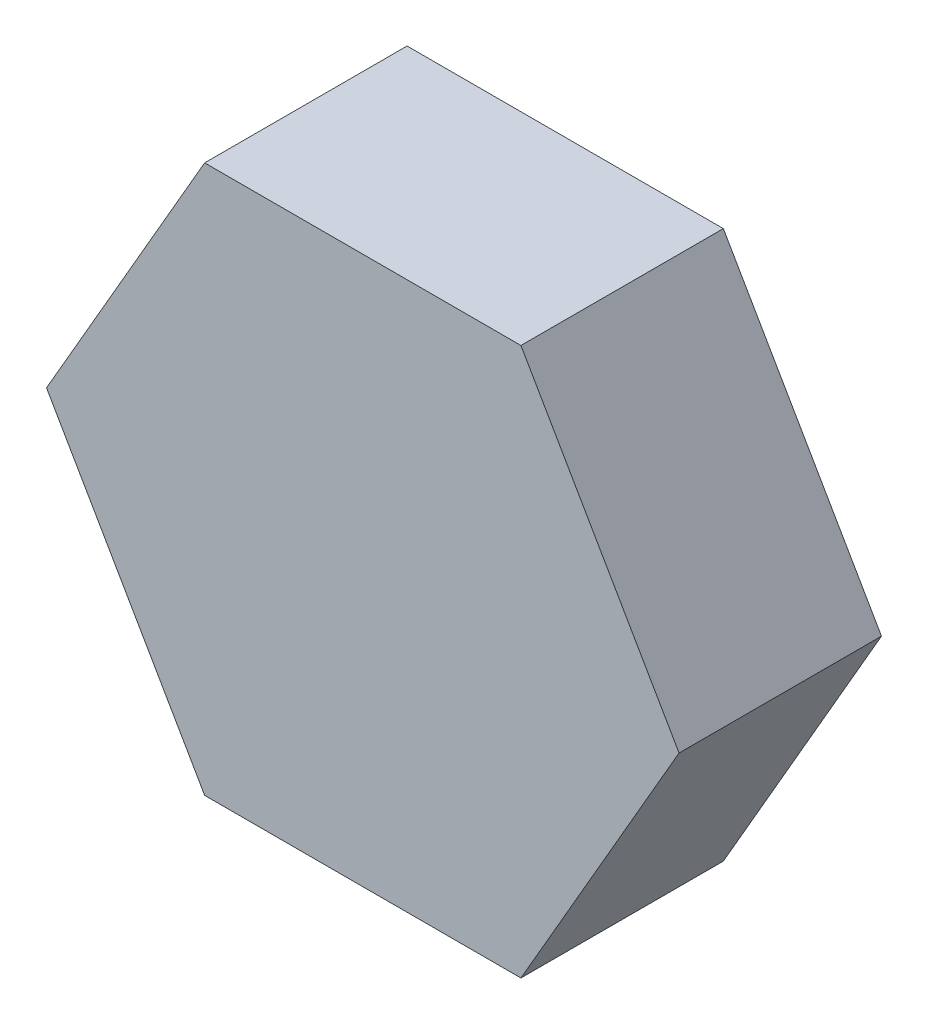
SolidWorks part; units mm, degrees
ref_plane "Plan de face" through (0, 0, 0) normal (0, 0, 1) x (1, 0, 0)
ref_plane "Plan de dessus" through (0, 0, 0) normal (0, 1, 0) x (1, 0, 0)
ref_plane "Plan de droite" through (0, 0, 0) normal (1, 0, 0) x (0, 0, -1)
sketch "Esquisse2" plane through (0, 0, 0) normal (0, 0, 1) x (1, 0, 0)
  line L1 (37.5, 0) -> (18.75, 32.476)
  line L2 (18.75, 32.476) -> (-18.75, 32.476)
  line L3 (-18.75, 32.476) -> (-37.5, 0)
  line L4 (-37.5, 0) -> (-18.75, -32.476)
  line L5 (-18.75, -32.476) -> (18.75, -32.476)
  line L6 (18.75, -32.476) -> (37.5, 0)
  circle A0 centre (0, 0) radius 32.476 construction
  dimension "D1" = 75
extrude "Boss.-Extru.1" add sketch "Esquisse2" along normal blind 24
